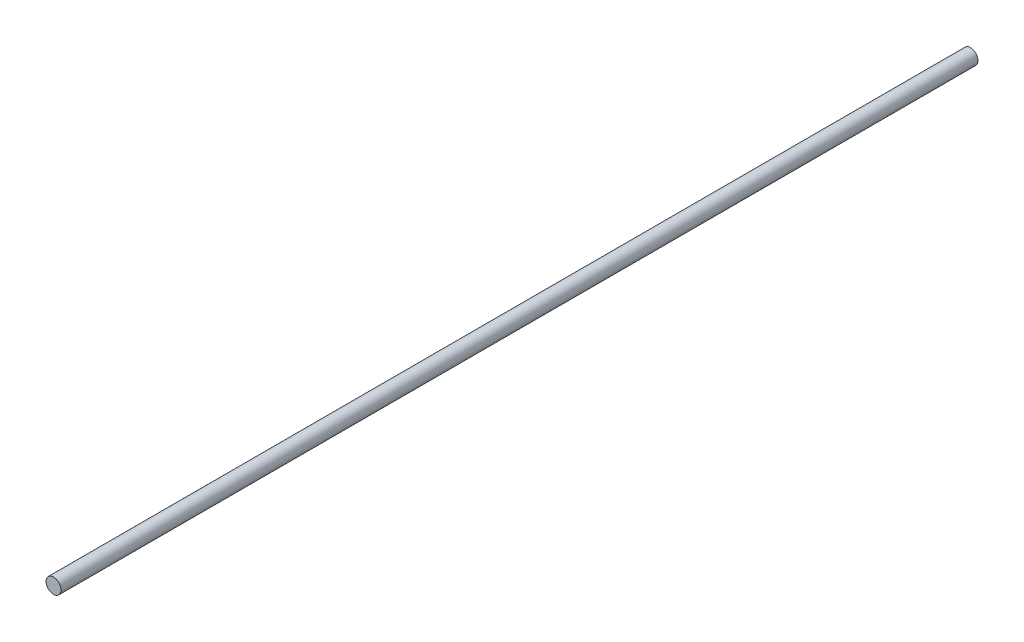
SolidWorks part; units mm, degrees
material "AISI 1020"
ref_plane "Front Plane" through (0, 0, 0) normal (0, 0, 1) x (1, 0, 0)
ref_plane "Top Plane" through (0, 0, 0) normal (0, 1, 0) x (1, 0, 0)
ref_plane "Right Plane" through (0, 0, 0) normal (1, 0, 0) x (0, 0, -1)
sketch "Sketch1" plane through (0, 0, 0) normal (0, 0, 1) x (1, 0, 0)
  circle A0 centre (0, 0) radius 6.0325
  dimension "D1" = 12.065
extrude "Boss-Extrude1" add sketch "Sketch1" along normal blind 736.6
